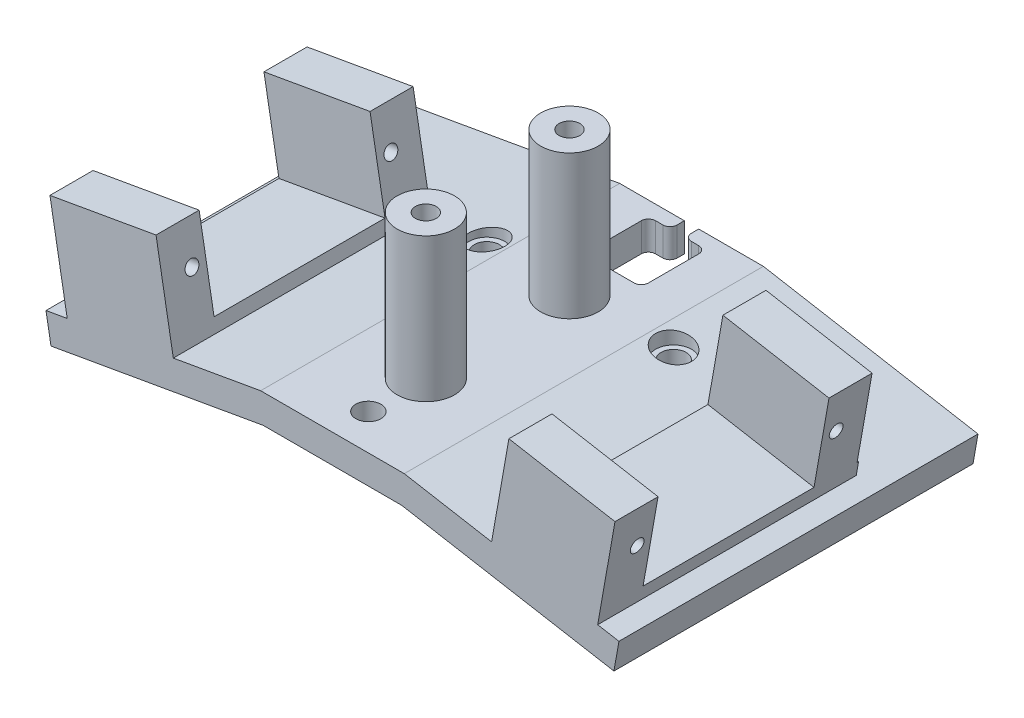
SolidWorks part; units mm, degrees
ref_plane "前视基准面" through (0, 0, 0) normal (0, 0, 1) x (1, 0, 0)
ref_plane "上视基准面" through (0, 0, 0) normal (0, 1, 0) x (1, 0, 0)
ref_plane "右视基准面" through (0, 0, 0) normal (1, 0, 0) x (0, 0, -1)
other "Configuration Table"
sketch "草图1" plane through (0, 0, 0) normal (0, 0, 1) x (1, 0, 0)
  line L0 (0, 0) -> (9.65, 0)
  line L1 (9.65, 0) -> (39.1943, -5.2094)
  line L2 (39.1943, -5.2094) -> (39.8889, -1.2702)
  line L3 (39.8889, -1.2702) -> (10, 4)
  line L4 (10, 4) -> (0, 4)
  line L5 (0, 4) -> (0, 0)
  dimension "D1" = 4
  dimension "D2" = 30
  dimension "D3" = 10
  dimension "D4" = 4
  dimension "D5" = 190
extrude "凸台-拉伸1" add sketch "草图1" along normal mid plane 50
sketch "草图2" plane through (0, 0, 25) normal (0, 0, 1) x (1, 0, 0)
  line L0 (22.1623, 1.8555) -> (22.4836, 3.6773)
  line L1 (39.8889, -1.2702) -> (10, 4) construction
  line L2 (22.4836, 3.6773) -> (37.2557, 1.0726)
  line L3 (37.2557, 1.0726) -> (36.9344, -0.7493)
  line L4 (36.9344, -0.7493) -> (22.1623, 1.8555)
  line L5 (39.1943, -5.2094) -> (39.8889, -1.2702) construction
  dimension "D1" = 1.85
  dimension "D2" = 18
  dimension "D3" = 15
extrude "凸台-拉伸2" add sketch "草图2" against normal blind 36
sketch "草图3" plane through (1.3068, 7.4114, 0) normal (0.1736, 0.9848, 0) x (0.9848, -0.1736, 0)
  line L0 (36.5034, 11) -> (36.5034, -25) construction
  line L1 (21.5034, -19) -> (36.5034, -19)
  line L2 (21.5034, -19) -> (21.5034, -25)
  line L3 (21.5034, -25) -> (36.5034, -25)
  line L4 (36.5034, -19) -> (36.5034, -25)
  line L5 (21.5034, 11) -> (21.5034, -25) construction
  line L6 (36.5034, 11) -> (36.5034, -25) construction
  line L7 (21.5034, 10.8) -> (36.5034, 10.8)
  line L8 (21.5034, 10.8) -> (21.5034, 4.8)
  line L9 (21.5034, 4.8) -> (36.5034, 4.8)
  line L10 (36.5034, 10.8) -> (36.5034, 4.8)
  line L11 (39.5034, -25) -> (36.5034, -25) construction
  dimension "D1" = 6
  dimension "D2" = 6
  dimension "D3" = 23.8
extrude "凸台-拉伸3" add sketch "草图3" along normal blind 12
sketch "草图4" plane through (35.9489, -6.3388, 0) normal (0.9848, -0.1736, 0) x (0, 0, -1)
  line L0 (4.8, 7.5257) -> (-19, 7.5257) construction
  line L1 (-19, 19.5257) -> (-19, 7.5257) construction
  line L2 (4.8, 19.5257) -> (4.8, 7.5257) construction
  circle A0 centre (-20.95, 14.0257) radius 0.95
  circle A1 centre (6.75, 14.0257) radius 0.95
  dimension "D1" = 6.5
  dimension "D2" = 6.5
  dimension "D3" = 1.95
  dimension "D4" = 1.95
  dimension "D5" = 1.9
  dimension "D6" = 1.9
extrude "切除-拉伸1" cut sketch "草图4" against normal blind 21
mirror "镜向1" about plane through (0, 0, 0) normal (1, 0, 0) of "切除-拉伸1", "凸台-拉伸3", "凸台-拉伸2", "凸台-拉伸1"
sketch "草图5" plane through (0, 4, 0) normal (0, 1, 0) x (1, 0, 0)
  circle A0 centre (0, -12) radius 4
  circle A1 centre (0, 8) radius 4
  circle A2 centre (0, 8) radius 1.45
  circle A3 centre (0, -12) radius 1.45
  dimension "D2" = 12
  dimension "D3" = 8
  dimension "D4" = 8
  dimension "D5" = 2.9
  dimension "D6" = 2.9
  dimension "D1" = 20
extrude "凸台-拉伸4" add sketch "草图5" along normal blind 20
sketch "草图6" plane through (0, 4, 0) normal (0, 1, 0) x (1, 0, 0)
  circle A0 centre (0, -20) radius 1.75
  circle A1 centre (-13, 9.5) radius 1.75
  circle A2 centre (13, 9.5) radius 1.75
  dimension "D1" = 20
  dimension "D2" = 26
  dimension "D3" = 29.5
  dimension "D4" = 3.5
  dimension "D5" = 13
extrude "切除-拉伸2" cut sketch "草图6" against normal blind 20
sketch "草图7" plane through (0, 4, 0) normal (0, 1, 0) x (1, 0, 0)
  circle A0 centre (-13, 9.5) radius 2.5
  circle A1 centre (13, 9.5) radius 2.5
  circle A2 centre (13, 9.5) radius 1.75 construction
  dimension "D1" = 5
extrude "切除-拉伸3" cut sketch "草图7" against normal blind 2
sketch "草图8" plane through (0, 4, 0) normal (0, 1, 0) x (1, 0, 0)
  line L0 (10, 25) -> (-10, 25) construction
  line L1 (-4, 23) -> (-1, 23)
  line L2 (-4, 23) -> (-4, 14)
  line L3 (-4, 14) -> (4, 14)
  line L4 (4, 23) -> (4, 14)
  line L5 (-4, 23) -> (4, 14) construction
  line L6 (-4, 14) -> (4, 23) construction
  line L7 (-1, 25) -> (1, 25)
  line L8 (-1, 25) -> (-1, 23)
  line L10 (1, 25) -> (1, 23)
  line L11 (1, 23) -> (4, 23)
  point P0 (0, 18.5)
  point P12 (0, 25)
  dimension "D1" = 8
  dimension "D2" = 9
  dimension "D3" = 14
  dimension "D4" = 2
extrude "切除-拉伸4" cut sketch "草图8" against normal through all
fillet "圆角4" radius 1 6 edges at (4, 2, -23) (-4, 2, -23) (1, 2, -23) (-1, 2, -23) (-4, 2, -14) (4, 2, -14)
